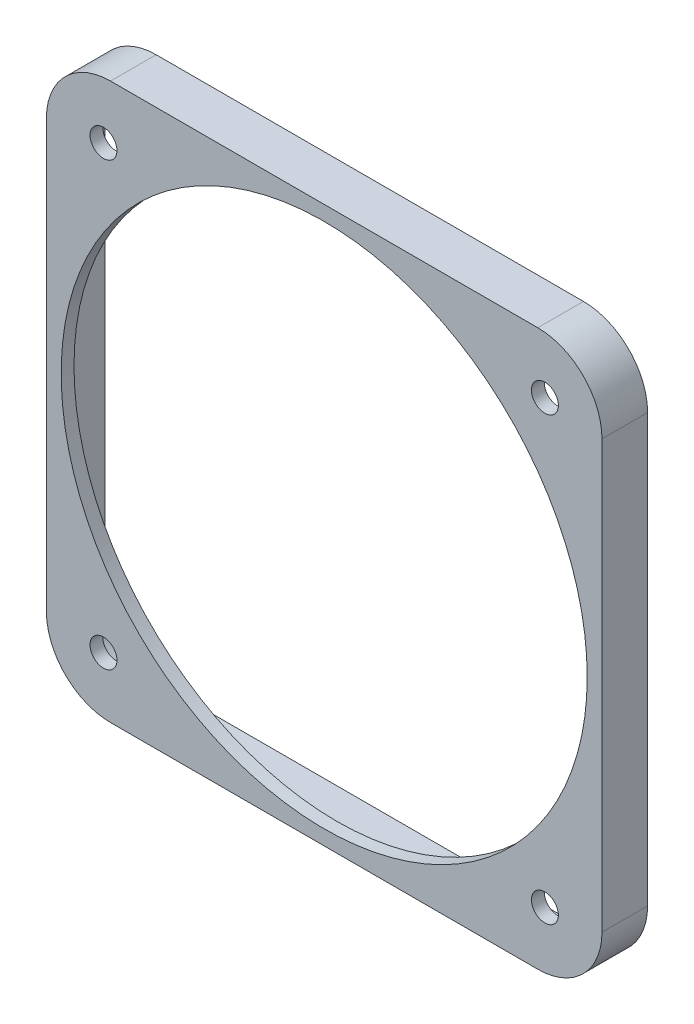
SolidWorks part; units mm, degrees
ref_plane "Front Plane" through (0, 0, 0) normal (0, 0, 1) x (1, 0, 0)
ref_plane "Top Plane" through (0, 0, 0) normal (0, 1, 0) x (1, 0, 0)
ref_plane "Right Plane" through (0, 0, 0) normal (1, 0, 0) x (0, 0, -1)
sketch "Sketch1" plane through (0, 0, 0) normal (0, 0, 1) x (1, 0, 0)
  line L1 (-54.991, -54.991) -> (54.991, -54.991)
  line L2 (-54.991, -54.991) -> (-54.991, 54.991)
  line L3 (-54.991, 54.991) -> (54.991, 54.991)
  line L4 (54.991, -54.991) -> (54.991, 54.991)
  line L5 (-54.991, -54.991) -> (54.991, 54.991) construction
  line L6 (-54.991, 54.991) -> (54.991, -54.991) construction
  point P0 (0, 0)
  dimension "D1" = 109.982
  dimension "D2" = 109.982
extrude "Boss-Extrude1" add sketch "Sketch1" along normal blind 9.0297
fillet "Fillet1" radius 12.7 4 edges at (54.991, -54.991, 4.5149) (-54.991, -54.991, 4.5149) (-54.991, 54.991, 4.5149) (54.991, 54.991, 4.5149)
shell "Shell1" thickness 2.54
sketch "Sketch2" plane through (0, 0, 9.0297) normal (0, 0, 1) x (1, 0, 0)
  line L0 (54.991, -42.291) -> (54.991, 42.291) construction
  line L1 (42.291, 54.991) -> (-42.291, 54.991) construction
  line L2 (-42.291, -54.991) -> (42.291, -54.991) construction
  line L3 (-54.991, 42.291) -> (-54.991, -42.291) construction
  circle A0 centre (0, 0) radius 52.07
  circle A1 centre (43.688, 43.688) radius 2.667
  circle A2 centre (-43.688, 43.688) radius 2.667
  circle A3 centre (-43.688, -43.688) radius 2.667
  circle A4 centre (43.688, -43.688) radius 2.667
  dimension "D1" = 5.334
  dimension "D6" = 104.14
  dimension "D2" = 11.303
  dimension "D3" = 11.303
  dimension "D4" = 11.303
  dimension "D5" = 11.303
extrude "Cut-Extrude1" cut sketch "Sketch2" against normal through all
